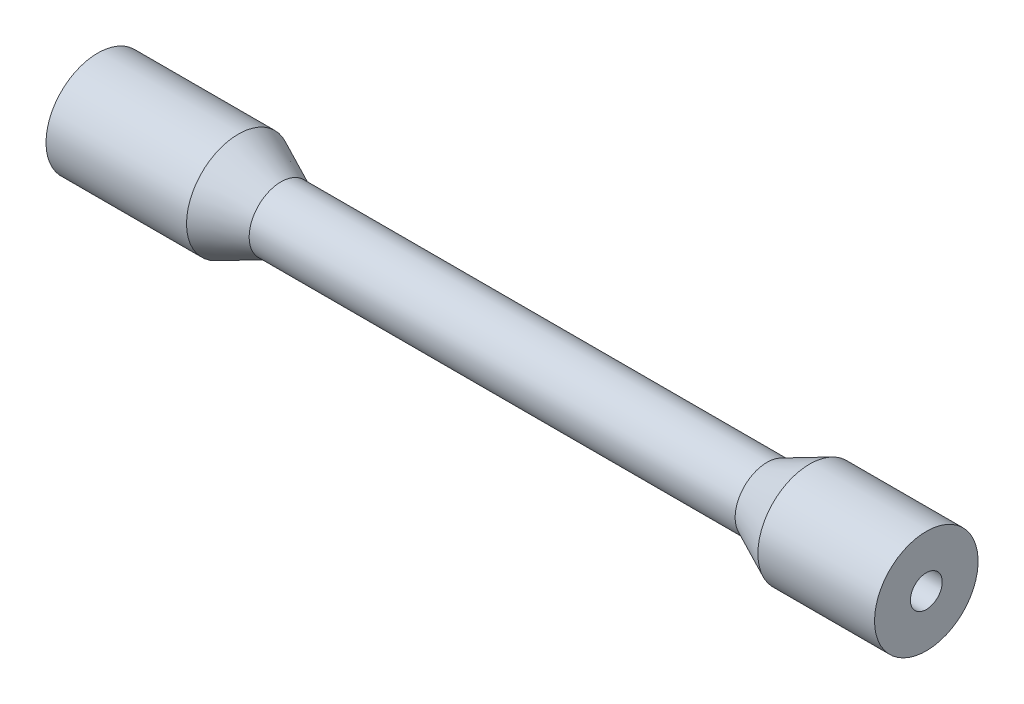
SolidWorks part; units mm, degrees
ref_plane "前视基准面" through (0, 0, 0) normal (0, 0, 1) x (1, 0, 0)
ref_plane "上视基准面" through (0, 0, 0) normal (0, 1, 0) x (1, 0, 0)
ref_plane "右视基准面" through (0, 0, 0) normal (1, 0, 0) x (0, 0, -1)
other "Configuration Table"
sketch "草图1" plane through (0, 0, 0) normal (1, 0, 0) x (0, 0, -1)
  circle A0 centre (0, 0) radius 1
  circle A1 centre (0, 0) radius 3.25
  dimension "D1" = 2
  dimension "D2" = 6.5
extrude "凸台-拉伸1" add sketch "草图1" along normal blind 52
sketch "草图3" plane through (0, 0, 0) normal (0, 0, 1) x (1, 0, 0)
  line L0 (8.8194, 3.25) -> (11.5, 2)
  line L1 (52, 3.25) -> (0, 3.25) construction
  line L2 (11.5, 2) -> (42, 2)
  line L3 (42, 2) -> (44.6806, 3.25)
  line L4 (44.6806, 3.25) -> (8.8194, 3.25)
  line L5 (26.75, 2) -> (26.75, 3.25) construction
  line L6 (0, 0) -> (52, 0) construction
  line L7 (52, -3.25) -> (52, 3.25) construction
  dimension "D1" = 10
  dimension "D2" = 155
  dimension "D3" = 30.5
  dimension "D4" = 4
revolve "切除-旋转1" cut sketch "草图3" angle 360 about L6
